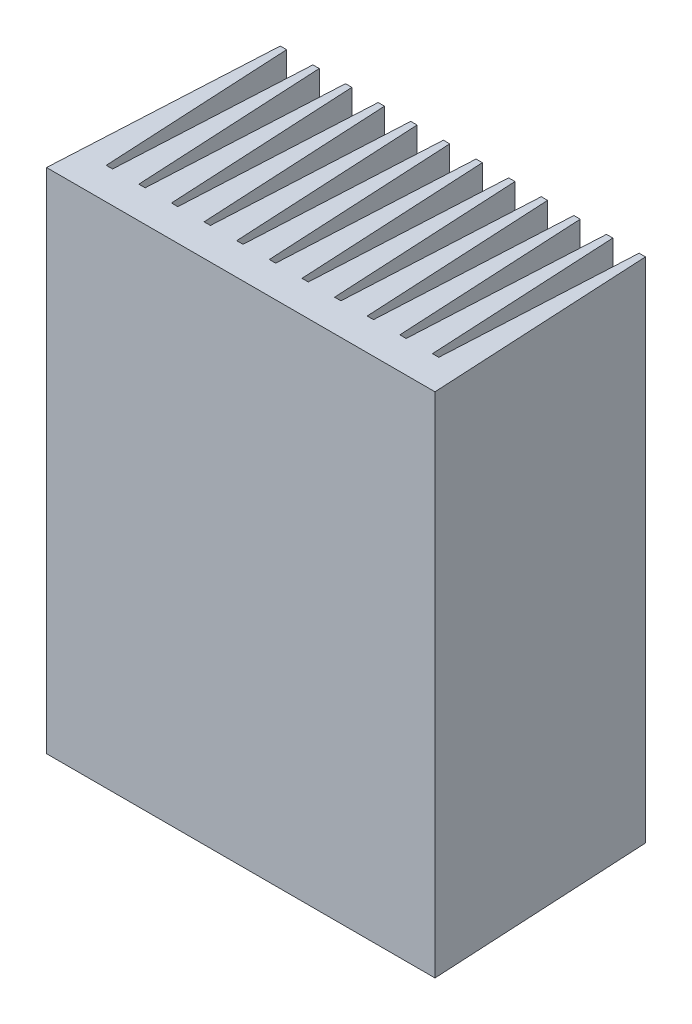
SolidWorks part; units mm, degrees
ref_plane "Front Plane" through (0, 0, 0) normal (0, 0, 1) x (1, 0, 0)
ref_plane "Top Plane" through (0, 0, 0) normal (0, 1, 0) x (1, 0, 0)
ref_plane "Right Plane" through (0, 0, 0) normal (1, 0, 0) x (0, 0, -1)
sketch "Sketch1" plane through (0, 0, 0) normal (0, 1, 0) x (1, 0, 0)
  line L0 (0, 0) -> (0, 5)
  line L1 (0, 5) -> (0.5, 5)
  line L2 (0.5, 5) -> (2.0722, 35)
  line L3 (2.0722, 35) -> (3.0722, 35)
  line L4 (3.0722, 35) -> (4.6445, 5)
  line L5 (4.6445, 5) -> (5.1445, 5)
  line L6 (2.5722, 35) -> (2.5722, -3.4863) construction
  line L7 (0, 5) -> (0, 40.4083) construction
  line L8 (5.14, 5) -> (5.64, 5)
  line L9 (5.64, 5) -> (7.2122, 35)
  line L10 (8.2122, 35) -> (9.7845, 5)
  line L11 (9.7845, 5) -> (10.2845, 5)
  line L12 (7.2122, 35) -> (8.2122, 35)
  line L13 (10.28, 5) -> (10.78, 5)
  line L14 (10.78, 5) -> (12.3522, 35)
  line L15 (13.3522, 35) -> (14.9245, 5)
  line L16 (14.9245, 5) -> (15.4245, 5)
  line L17 (12.3522, 35) -> (13.3522, 35)
  line L18 (15.42, 5) -> (15.92, 5)
  line L19 (15.92, 5) -> (17.4922, 35)
  line L20 (18.4922, 35) -> (20.0645, 5)
  line L21 (20.0645, 5) -> (20.5645, 5)
  line L22 (17.4922, 35) -> (18.4922, 35)
  line L23 (20.56, 5) -> (21.06, 5)
  line L24 (21.06, 5) -> (22.6322, 35)
  line L25 (23.6322, 35) -> (25.2045, 5)
  line L26 (25.2045, 5) -> (25.7045, 5)
  line L27 (22.6322, 35) -> (23.6322, 35)
  line L28 (25.7, 5) -> (26.2, 5)
  line L29 (26.2, 5) -> (27.7722, 35)
  line L30 (28.7722, 35) -> (30.6065, 0)
  line L32 (27.7722, 35) -> (28.7722, 35)
  line L33 (0, 5) -> (5.14, 5) construction
  line L34 (30.3445, 5) -> (30.8445, 5) [skipped]
  line L35 (30.6065, 0) -> (0, 0)
  line L37 (28.7722, 35) -> (30.3445, 5) [skipped]
  dimension "D1" = 35
  dimension "D2" = 1
  dimension "D3" = 5
  dimension "D4" = 0.5
  dimension "D5" = 0.5
  dimension "D6" = 93
  dimension "D7" = 5.1445
  dimension "D9" = 5.14
  dimension "D8" = 6
extrude "Boss-Extrude1" add sketch "Sketch1" against normal blind 80 contours L35 L30 L32 L29 L28 L26 L25 L27 L24 L23 L21 L20 L22 L19 L18 L16 L15 L17 L14 L13 L11 L10 L12 L9 L8 L5 L4 L3 L2 L1 L0
mirror "Mirror1" about plane through (0, -80, 0) normal (1, 0, 0) of "Boss-Extrude1"
